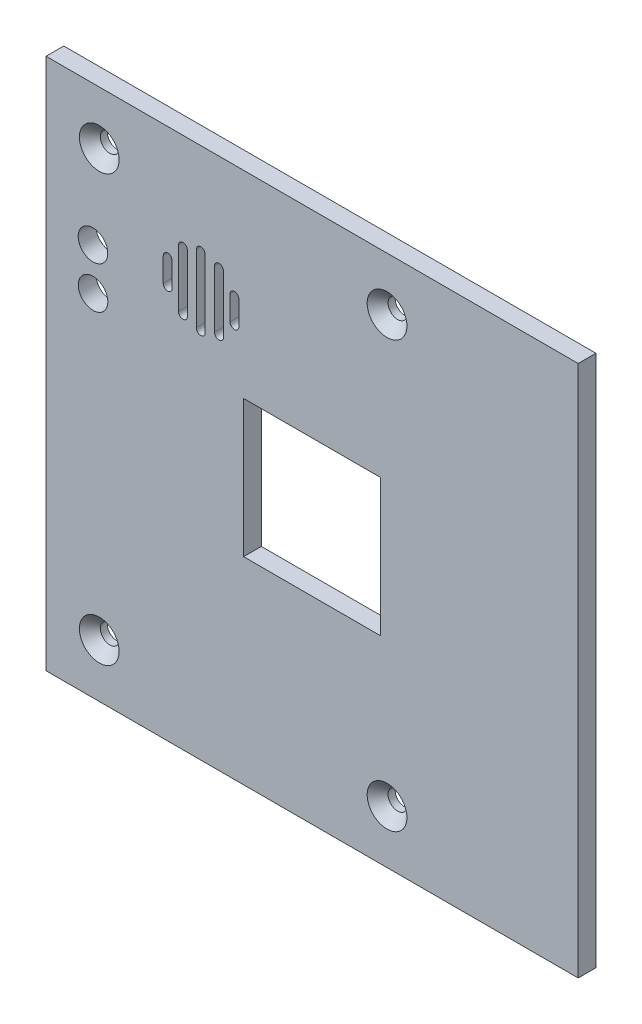
SolidWorks part; units mm, degrees
ref_plane "Alzado" through (0, 0, 0) normal (0, 0, 1) x (1, 0, 0)
ref_plane "Planta" through (0, 0, 0) normal (0, 1, 0) x (1, 0, 0)
ref_plane "Vista lateral" through (0, 0, 0) normal (1, 0, 0) x (0, 0, -1)
sketch "Croquis1" plane through (0, 0, 0) normal (0, 0, 1) x (1, 0, 0)
  line L0 (-12.0434, 27.6739) -> (-12.0434, 16.1739) construction
  line L1 (-38.2095, 43.2389) -> (51.7905, 43.2389)
  line L2 (-38.2095, 43.2389) -> (-38.2095, -46.7611)
  line L3 (-38.2095, -46.7611) -> (51.7905, -46.7611)
  line L4 (51.7905, 43.2389) -> (51.7905, -46.7611)
  line L9 (-4.7995, 9.8289) -> (18.3805, 9.8289)
  line L10 (-4.7995, 9.8289) -> (-4.7995, -13.3511)
  line L11 (-4.7995, -13.3511) -> (18.3805, -13.3511)
  line L12 (18.3805, 9.8289) -> (18.3805, -13.3511)
  line L13 (-11.2934, 27.6739) -> (-11.2934, 16.1739)
  line L14 (-12.7934, 27.6739) -> (-12.7934, 16.1739)
  line L15 (-11.2934, 21.9239) -> (-9.8126, 21.9239) construction
  line L16 (-12.7934, 21.9239) -> (-14.1813, 21.9239) construction
  line L17 (-15.059, 26.7941) -> (-15.059, 17.0537) construction
  line L18 (-14.309, 26.7941) -> (-14.309, 17.0537)
  line L19 (-15.809, 26.7941) -> (-15.809, 17.0537)
  line L20 (-8.96, 26.7941) -> (-8.96, 17.0537) construction
  line L21 (-8.21, 26.7941) -> (-8.21, 17.0537)
  line L22 (-9.71, 26.7941) -> (-9.71, 17.0537)
  line L23 (-17.6395, 23.9639) -> (-17.6395, 19.8839) construction
  line L24 (-16.8895, 23.9639) -> (-16.8895, 19.8839)
  line L25 (-18.3895, 23.9639) -> (-18.3895, 19.8839)
  line L26 (-6.3544, 23.9639) -> (-6.3544, 19.8839) construction
  line L27 (-5.6044, 23.9639) -> (-5.6044, 19.8839)
  line L28 (-7.1044, 23.9639) -> (-7.1044, 19.8839)
  circle A0 centre (-30.2723, 19.5848) radius 2.5
  circle A1 centre (-30.2627, 12.4865) radius 2.5
  circle A2 centre (-29.2095, 34.2389) radius 1.625
  circle A3 centre (19.4591, 34.2389) radius 1.625
  circle A4 centre (-29.2095, -37.7611) radius 1.625
  circle A5 centre (19.4591, -37.7611) radius 1.625
  circle A6 centre (-11.997, 21.9239) radius 6 construction
  arc A7 (-11.2934, 27.6739) -> (-12.7934, 27.6739) centre (-12.0434, 27.6739) ccw
  arc A8 (-12.7934, 16.1739) -> (-11.2934, 16.1739) centre (-12.0434, 16.1739) ccw
  arc A9 (-14.309, 26.7941) -> (-15.809, 26.7941) centre (-15.059, 26.7941) ccw
  arc A10 (-15.809, 17.0537) -> (-14.309, 17.0537) centre (-15.059, 17.0537) ccw
  arc A11 (-8.21, 26.7941) -> (-9.71, 26.7941) centre (-8.96, 26.7941) ccw
  arc A12 (-9.71, 17.0537) -> (-8.21, 17.0537) centre (-8.96, 17.0537) ccw
  arc A13 (-16.8895, 23.9639) -> (-18.3895, 23.9639) centre (-17.6395, 23.9639) ccw
  arc A14 (-18.3895, 19.8839) -> (-16.8895, 19.8839) centre (-17.6395, 19.8839) ccw
  arc A15 (-5.6044, 23.9639) -> (-7.1044, 23.9639) centre (-6.3544, 23.9639) ccw
  arc A16 (-7.1044, 19.8839) -> (-5.6044, 19.8839) centre (-6.3544, 19.8839) ccw
  point P25 (-12.0434, 21.9239)
  point P36 (-15.059, 21.9239)
  point P41 (-8.96, 21.9239)
  point P50 (-17.6395, 21.9239)
  point P57 (-6.3544, 21.9239)
  point P62 (0, 0)
  dimension "D1" = 5
  dimension "D2" = 3.25
  dimension "D3" = 12
  dimension "D19" = 0.75
  dimension "D4" = 18.3805
  dimension "D5" = 19.4591
  dimension "D6" = 51.7905
  dimension "D7" = 4.7995
  dimension "D8" = 11.997
  dimension "D9" = 29.2095
  dimension "D10" = 30.2627
  dimension "D11" = 30.2723
  dimension "D12" = 38.2095
  dimension "D13" = 9.8289
  dimension "D14" = 12.4865
  dimension "D15" = 19.5848
  dimension "D16" = 21.9239
  dimension "D17" = 34.2389
  dimension "D18" = 43.2389
  dimension "D20" = 37.7611
  dimension "D21" = 6.3544
  dimension "D22" = 8.96
  dimension "D23" = 12.0434
  dimension "D24" = 15.059
  dimension "D25" = 16.1739
  dimension "D26" = 17.0537
extrude "Saliente-Extruir1" add sketch "Croquis1" along normal blind 3
sketch "Croquis2" plane through (0, 0, 3) normal (0, 0, 1) x (1, 0, 0)
  line L0 (51.7905, -46.7611) -> (51.7905, 43.2389) construction
  line L1 (-38.2095, -46.7611) -> (51.7905, -46.7611) construction
  circle A0 centre (-29.2095, 34.2389) radius 3.36
  circle A1 centre (19.4591, 34.2389) radius 3.36
  circle A2 centre (19.4591, -37.7611) radius 3.36
  circle A3 centre (-29.2095, -37.7611) radius 3.36
  dimension "D1" = 6.7199
  dimension "D2" = 32.3314
  dimension "D3" = 81
  dimension "D4" = 9
  dimension "D5" = 81
extrude "Cortar-Extruir1" cut sketch "Croquis2" against normal blind 1.8 draft 44
